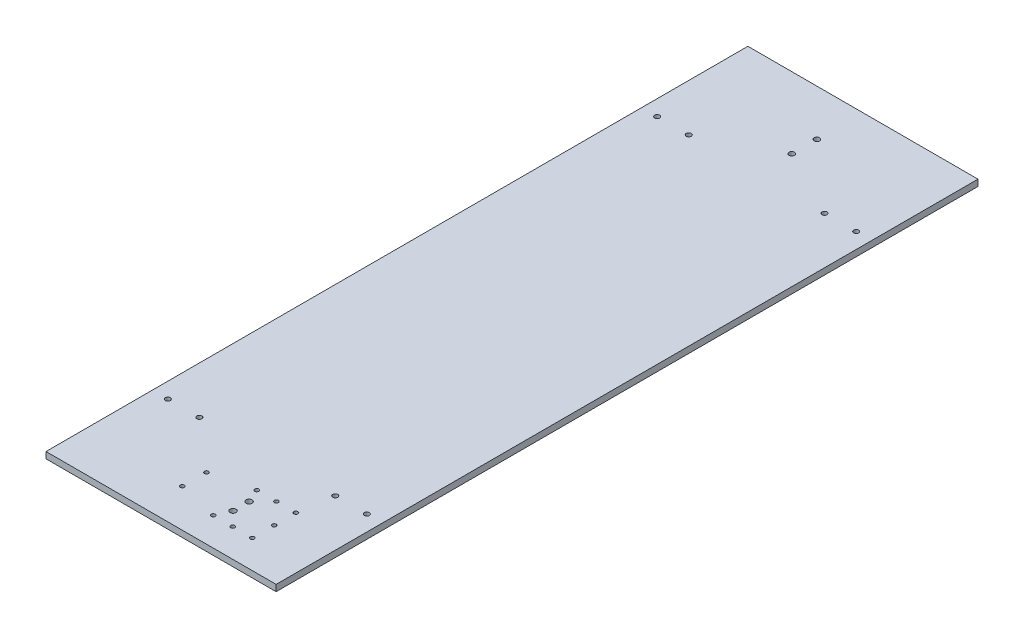
SolidWorks part; units mm, degrees
material "Pin"
ref_plane "Plan de face" through (0, 0, 0) normal (0, 0, 1) x (1, 0, 0)
ref_plane "Plan de dessus" through (0, 0, 0) normal (0, 1, 0) x (1, 0, 0)
ref_plane "Plan de droite" through (0, 0, 0) normal (1, 0, 0) x (0, 0, -1)
sketch "Esquisse1" plane through (0, 0, 0) normal (0, 1, 0) x (1, 0, 0)
  line L1 (114.75, 350) -> (-114.75, 350)
  line L2 (114.75, 350) -> (114.75, -350)
  line L3 (114.75, -350) -> (-114.75, -350)
  line L4 (-114.75, 350) -> (-114.75, -350)
  line L5 (114.75, 350) -> (-114.75, -350) construction
  line L6 (114.75, -350) -> (-114.75, 350) construction
  point P0 (0, 0)
  dimension "D1" = 229.5
  dimension "D2" = 700
extrude "Boss.-Extru.1" add sketch "Esquisse1" along normal blind 6.35
sketch "Esquisse2" plane through (0, 0, 0) normal (0, -1, 0) x (1, 0, 0)
  line L0 (3.4925, 0) -> (-3.4925, 0) construction
  line L1 (0, -3.4925) -> (0, 3.4925) construction
  circle A0 centre (-16.75, 312) radius 2
  circle A1 centre (-16.75, 288) radius 2
  circle A2 centre (23.75, 321.75) radius 2
  circle A3 centre (23.75, 278.25) radius 2
  circle A4 centre (43.25, 278.25) radius 2
  circle A5 centre (43.25, 321.75) radius 2
  circle A6 centre (62.75, 321.75) radius 2
  circle A7 centre (62.75, 300) radius 2
  circle A8 centre (62.75, 278.25) radius 2
  circle A9 centre (29.75, 292) radius 3
  circle A10 centre (29.75, 308) radius 3
  circle A11 centre (67.75, 244) radius 2.5
  circle A12 centre (99.25, 244) radius 2.5
  circle A13 centre (67.75, -244) radius 2.5
  circle A14 centre (99.25, -244) radius 2.5
  circle A15 centre (-99.25, -244) radius 2.5
  circle A16 centre (-67.75, -244) radius 2.5
  circle A17 centre (-99.25, 244) radius 2.5
  circle A18 centre (-67.75, 244) radius 2.5
extrude "Enlèv. mat.-Extru.1" cut sketch "Esquisse2" against normal through all
sketch "Esquisse3" plane through (0, 6.35, 0) normal (0, 1, 0) x (1, 0, 0)
  circle A0 centre (0, 279) radius 2.75
  circle A1 centre (0, 304) radius 2.75
  circle A2 centre (67.75, 244) radius 2.5 construction
  point P7 (0, 0)
  point P8 (0, 0)
  point P9 (0, 0)
  point P10 (0, 304)
  dimension "D2" = 5.5
  dimension "D1" = 25
  dimension "D3" = 35
extrude "Enlèv. mat.-Extru.2" cut sketch "Esquisse3" against normal through all
